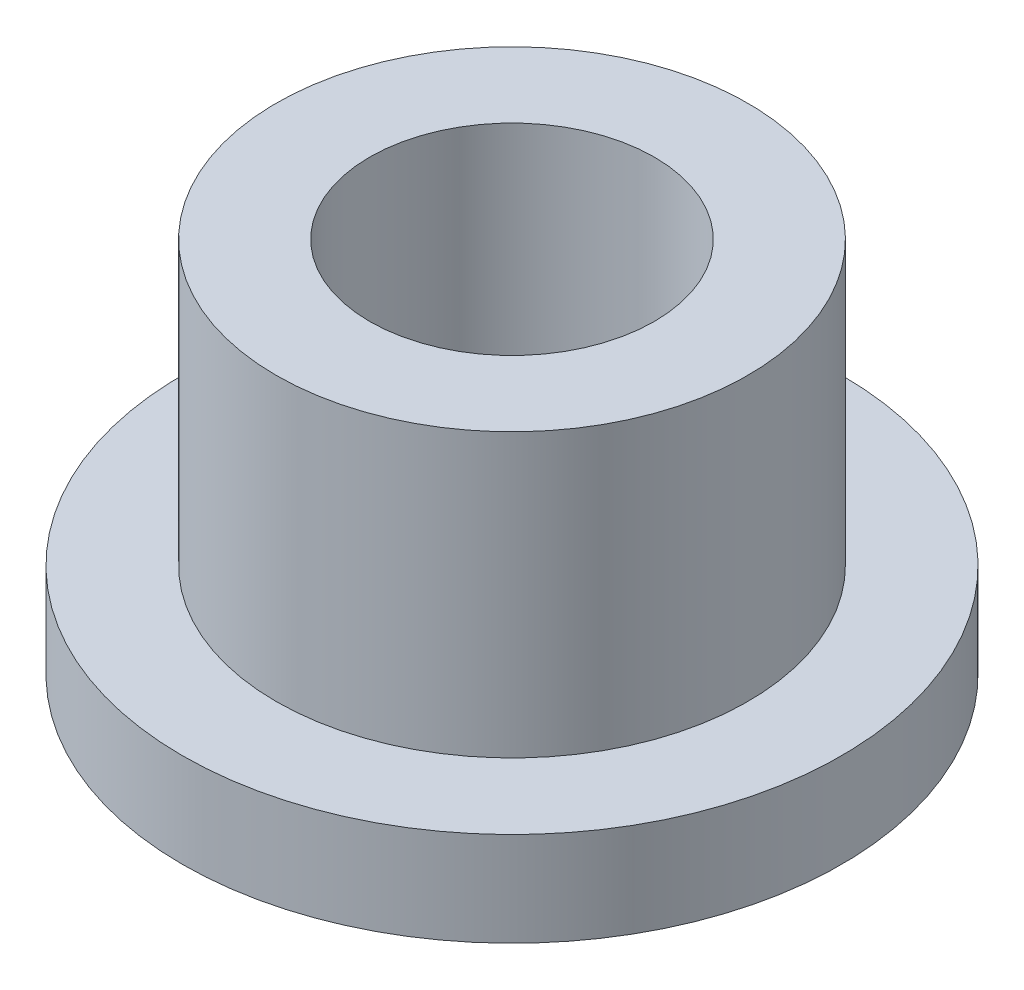
SolidWorks part; units mm, degrees
ref_plane "Front" through (0, 0, 0) normal (0, 0, 1) x (1, 0, 0)
ref_plane "Top" through (0, 0, 0) normal (0, 1, 0) x (1, 0, 0)
ref_plane "Right" through (0, 0, 0) normal (1, 0, 0) x (0, 0, -1)
sketch "Sketch1" plane through (0, 0, 0) normal (0, 1, 0) x (1, 0, 0)
  circle A0 centre (0, 0) radius 2.4003
  circle A1 centre (0, 0) radius 3.9751
  circle A2 centre (0, 0) radius 5.5562
  dimension "ID" = 4.8006
  dimension "OD" = 7.9502
  dimension "FlangeOD" = 11.1125
sketch "Sketch2" plane through (0, 0, 0) normal (0, 1, 0) x (1, 0, 0)
  circle A0 centre (0, 0) radius 2.4003 construction
  circle A1 centre (0, 0) radius 3.9751 construction
  circle A2 centre (0, 0) radius 2.4003
  circle A3 centre (0, 0) radius 3.9751
extrude "Boss-Extrude1" add sketch "Sketch2" along normal blind 6.35
sketch "Sketch3" plane through (0, 0, 0) normal (0, 1, 0) x (1, 0, 0)
  circle A0 centre (0, 0) radius 5.5562 construction
  circle A1 centre (0, 0) radius 3.9751 construction
  circle A2 centre (0, 0) radius 5.5562
  circle A3 centre (0, 0) radius 3.9751
extrude "Boss-Extrude2" add sketch "Sketch3" along normal blind 1.5875
